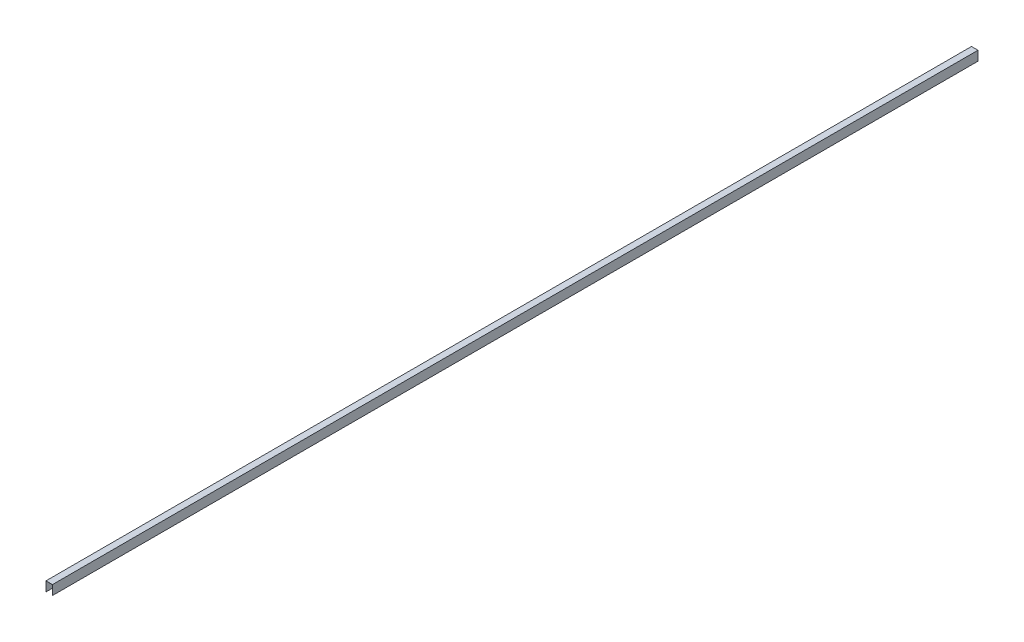
SolidWorks part; units mm, degrees
ref_plane "Front Plane" through (0, 0, 0) normal (0, 0, 1) x (1, 0, 0)
ref_plane "Top Plane" through (0, 0, 0) normal (0, 1, 0) x (1, 0, 0)
ref_plane "Right Plane" through (0, 0, 0) normal (1, 0, 0) x (0, 0, -1)
sketch "Sketch1" plane through (0, 0, 0) normal (0, 0, 1) x (1, 0, 0)
  line L0 (0, 0) -> (0, 19.304)
  line L1 (0, 19.304) -> (13.208, 19.304)
  line L2 (13.208, 19.304) -> (13.208, 0)
  line L3 (13.208, 0) -> (12.954, 0)
  line L4 (12.954, 0) -> (12.954, 19.05)
  line L5 (12.954, 19.05) -> (0.254, 19.05)
  line L6 (0.254, 19.05) -> (0.254, 0)
  line L7 (0.254, 0) -> (0, 0)
  line L8 (0.254, 19.05) -> (0.254, 19.304) construction
  dimension "D1" = 0.254
  dimension "D2" = 12.7
  dimension "D3" = 19.05
extrude "Boss-Extrude1" add sketch "Sketch1" along normal blind 1879.6
